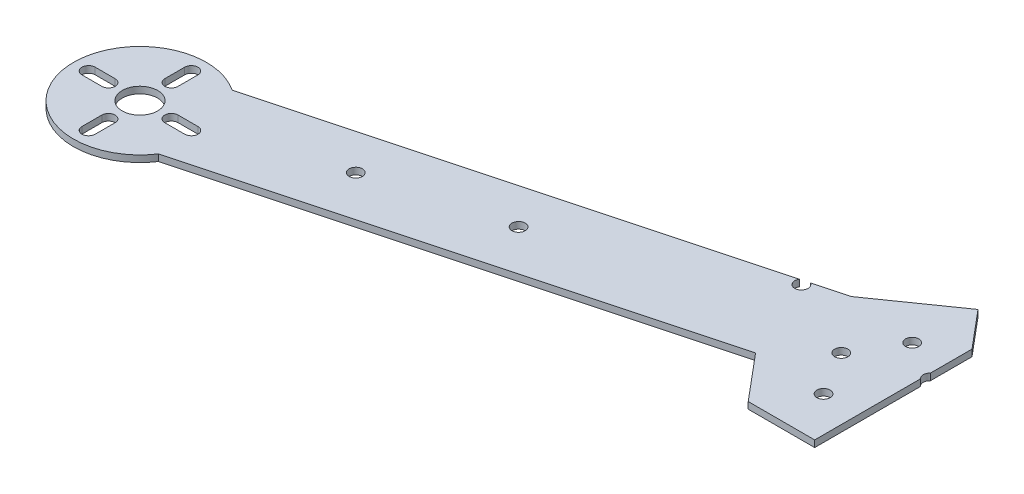
SolidWorks part; units mm, degrees
other "Markup1"
sketch "Sketch5" plane through (0, 1.5, 8.4265) normal (-0.2691, 0.6708, 0.6911) x (0.9345, 0.0084, 0.3557)
ref_plane "Front Plane" through (0, 0, 0) normal (0, 0, 1) x (1, 0, 0)
ref_plane "Top Plane" through (0, 0, 0) normal (0, 1, 0) x (1, 0, 0)
ref_plane "Right Plane" through (0, 0, 0) normal (1, 0, 0) x (0, 0, -1)
sketch "Sketch2" plane through (0, 0, 0) normal (0, 1, 0) x (1, 0, 0)
  line L7 (0, 0) -> (0, 15.3974) construction
  line L8 (-23.6776, -60.4195) -> (-23.8633, -38.593) construction
  line L9 (-136.0028, -80.5981) -> (-147.7774, -80.5981) construction
  line L10 (-147.7774, -80.5981) -> (-142.4295, -80.5981) construction
  line L11 (-142.4295, -80.5981) -> (-142.4295, -86.6558) construction
  line L12 (0, -35.2611) -> (0, -44.6431)
  line L17 (0, -70.7611) -> (-15, -70.7611)
  line L20 (-15, -70.7611) -> (-23.6776, -60.4195)
  line L23 (-23.6776, -60.4195) -> (-129.9295, -88.8896)
  line L25 (7.0707, -17.6306) -> (28.2625, -17.6306) construction
  line L51 (0, -35.2611) -> (-7.0707, -26.8346)
  line L52 (-7.0707, -26.8346) -> (-23.8633, -38.593)
  line L53 (-23.8633, -38.593) -> (-134.0979, -68.1247)
  line L54 (-142.4295, -80.5981) -> (-142.4295, -75.2609)
  line L55 (0, -46.8792) -> (0, -70.7611)
  line L56 (-135.3295, -80.5981) -> (-130.8295, -80.5981) construction
  line L57 (-135.3295, -79.0981) -> (-130.8295, -79.0981)
  line L58 (-135.3295, -82.0981) -> (-130.8295, -82.0981)
  line L59 (-142.4295, -87.6981) -> (-142.4295, -92.1981) construction
  line L60 (-140.9295, -87.6981) -> (-140.9295, -92.1981)
  line L61 (-143.9295, -87.6981) -> (-143.9295, -92.1981)
  line L62 (-149.5295, -80.5981) -> (-154.0295, -80.5981) construction
  line L63 (-149.5295, -82.0981) -> (-154.0295, -82.0981)
  line L64 (-149.5295, -79.0981) -> (-154.0295, -79.0981)
  line L65 (-142.4295, -73.4981) -> (-142.4295, -68.9981) construction
  line L66 (-143.9295, -73.4981) -> (-143.9295, -68.9981)
  line L67 (-140.9295, -73.4981) -> (-140.9295, -68.9981)
  arc A28 (-134.0979, -68.1247) -> (-129.9295, -88.8896) centre (-142.4295, -80.5981) ccw
  circle A29 centre (-142.4295, -80.5981) radius 4
  circle A30 centre (-8, -60.7611) radius 1.5
  circle A31 centre (-14, -50.7611) radius 1.5
  circle A32 centre (-8, -40.7611) radius 1.5
  arc A33 (0, -44.6431) -> (0, -46.8792) centre (1, -45.7611) ccw
  arc A34 (-135.3295, -79.0981) -> (-135.3295, -82.0981) centre (-135.3295, -80.5981) ccw
  arc A35 (-130.8295, -82.0981) -> (-130.8295, -79.0981) centre (-130.8295, -80.5981) ccw
  arc A36 (-140.9295, -87.6981) -> (-143.9295, -87.6981) centre (-142.4295, -87.6981) ccw
  arc A37 (-143.9295, -92.1981) -> (-140.9295, -92.1981) centre (-142.4295, -92.1981) ccw
  arc A38 (-149.5295, -82.0981) -> (-149.5295, -79.0981) centre (-149.5295, -80.5981) ccw
  arc A39 (-154.0295, -79.0981) -> (-154.0295, -82.0981) centre (-154.0295, -80.5981) ccw
  arc A40 (-143.9295, -73.4981) -> (-140.9295, -73.4981) centre (-142.4295, -73.4981) ccw
  arc A41 (-140.9295, -68.9981) -> (-143.9295, -68.9981) centre (-142.4295, -68.9981) ccw
  point P44 (-133.0795, -80.5981)
  point P52 (-142.4295, -89.9481)
  point P82 (-151.7795, -80.5981)
  point P92 (-142.4295, -71.2481)
  point P127 (-142.4295, -80.5981)
extrude "Boss-Extrude1" add sketch "Sketch2" along normal blind 1.5
sketch "Sketch6" plane through (0, 1.5, 0) normal (0, 1, 0) x (1, 0, 0)
  circle A0 centre (-31.86, -41.9011) radius 1.5
  circle A1 centre (-14, -50.7611) radius 1.5 construction
  dimension "D1" = 3
  dimension "D2" = 8.86
  dimension "D3" = 17.86
extrude "Cut-Extrude1" cut sketch "Sketch6" against normal up to surface (1.5 mm away) up to face at (-142.4295, 0, 71.2481)
sketch "Sketch7" plane through (0, 1.5, 0) normal (0, 1, 0) x (1, 0, 0)
  line L0 (-134.0979, -68.1247) -> (-23.8633, -38.593) construction
  line L1 (-142.4295, -80.5981) -> (-23.8791, -48.8385) construction
  circle A0 centre (-104.0141, -70.3066) radius 1.5
  circle A1 centre (-75.036, -62.5434) radius 1.5
  point P11 (-111.1346, -72.2142)
  point P12 (-77.9261, -63.3177)
  dimension "D1" = 3
  dimension "D2" = 3
  dimension "D3" = 30
  dimension "D4" = 39.77
extrude "Cut-Extrude2" cut sketch "Sketch7" against normal up to surface (1.5 mm away) up to face at (-142.4295, 0, 71.2481)
